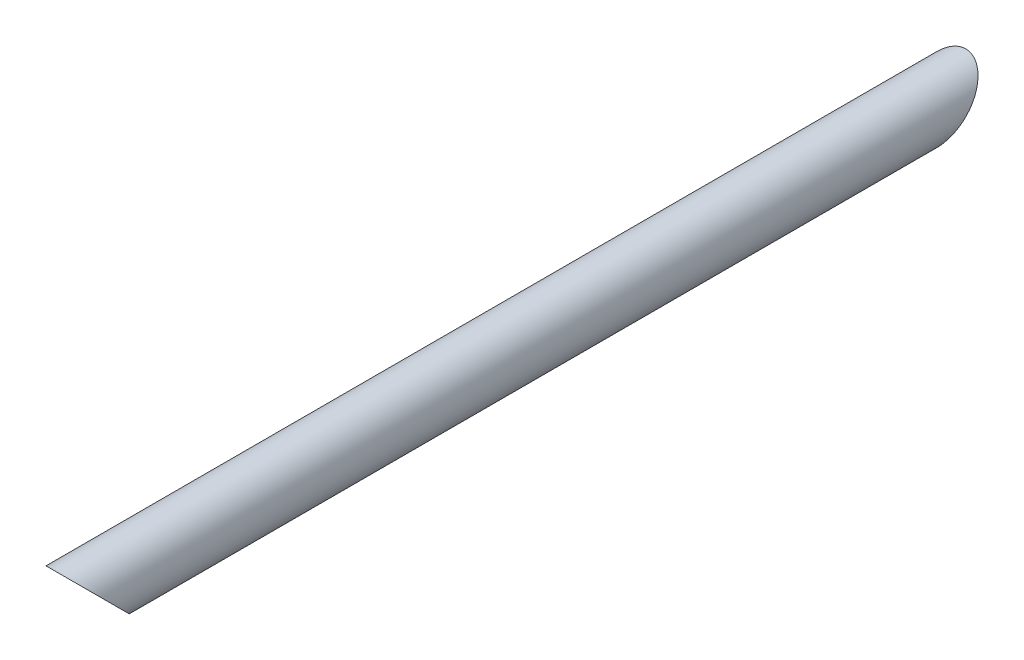
SolidWorks part; units mm, degrees
ref_plane "Front Plane" through (0, 0, 0) normal (0, 0, 1) x (1, 0, 0)
ref_plane "Top Plane" through (0, 0, 0) normal (0, 1, 0) x (1, 0, 0)
ref_plane "Right Plane" through (0, 0, 0) normal (1, 0, 0) x (0, 0, -1)
sketch "Sketch1" plane through (0, 0, 0) normal (0, 0, 1) x (1, 0, 0)
  circle A0 centre (-1.8943, 7.2614) radius 26.9875
  dimension "D1" = 53.975
extrude "Boss-Extrude1" add sketch "Sketch1" along normal blind 831.85 contours A0
sketch "Sketch2" plane through (0, 0, 0) normal (1, 0, 0) x (0, 0, -1)
  line L0 (-831.85, 34.2489) -> (-777.875, -19.7261)
  line L1 (-831.85, 34.2489) -> (-831.85, -19.7261) construction
  line L2 (-831.85, -19.7261) -> (0, -19.7261) construction
  line L3 (-777.875, -19.7261) -> (-831.85, -19.7261)
  line L4 (-831.85, -19.7261) -> (-831.85, 34.2489)
  line L5 (0, 34.2489) -> (-53.975, -19.7261)
  line L6 (-53.975, -19.7261) -> (0, -19.7261)
  line L7 (0, -19.7261) -> (0, 34.2489)
extrude "Cut-Extrude1" cut sketch "Sketch2" against normal through all both and the other way through all
ref_plane "Plane1" through (0, 0, 415.925) normal (0, 0, 1) x (1, 0, 0)
